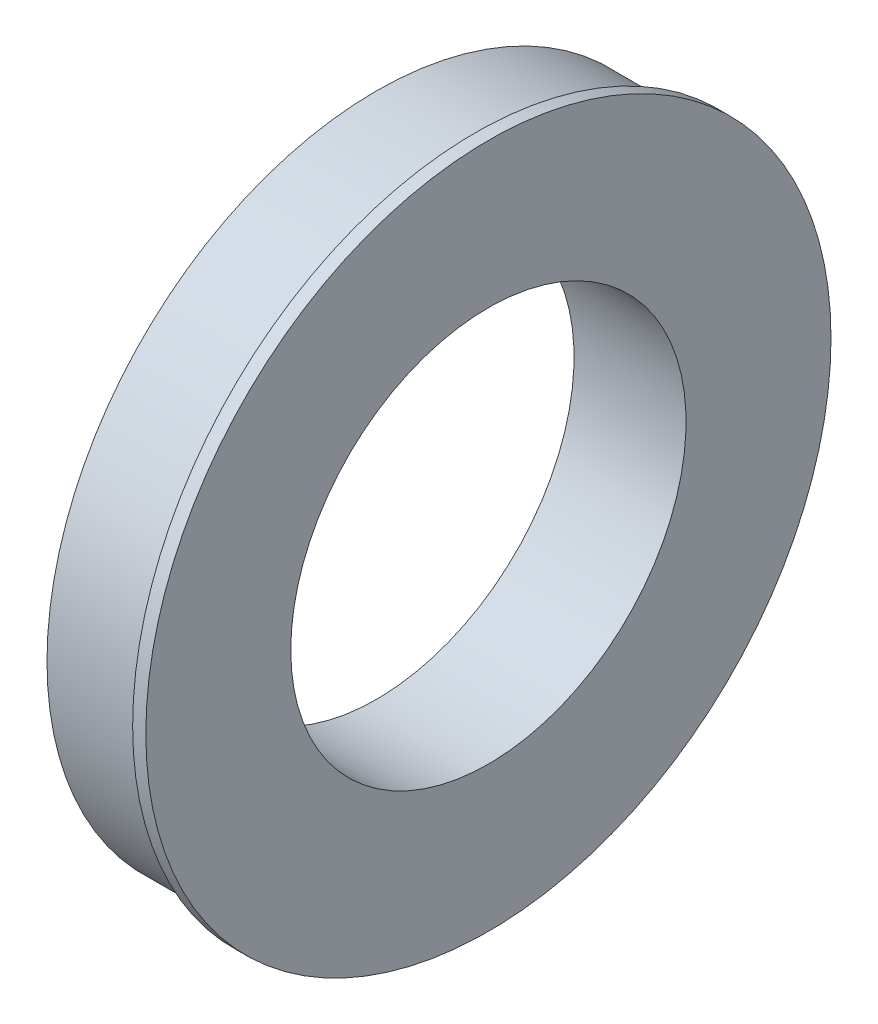
SolidWorks part; units mm, degrees
ref_plane "Front Plane" through (0, 0, 0) normal (0, 0, 1) x (1, 0, 0)
ref_plane "Top Plane" through (0, 0, 0) normal (0, 1, 0) x (1, 0, 0)
ref_plane "Right Plane" through (0, 0, 0) normal (1, 0, 0) x (0, 0, -1)
sketch "Sketch1" plane through (0, 0, 0) normal (1, 0, 0) x (0, 0, -1)
  circle A0 centre (0, 0) radius 63.5
  circle A1 centre (0, 0) radius 38.1
  dimension "D1" = 127
  dimension "D2" = 76.2
extrude "Boss-Extrude1" add sketch "Sketch1" along normal blind 19.05
sketch "Sketch2" plane through (19.05, 0, 0) normal (1, 0, 0) x (0, 0, -1)
  circle A1 centre (0, 0) radius 38.1 construction
  circle A2 centre (0, 0) radius 66.04
  circle A3 centre (0, 0) radius 66.04
  circle A4 centre (0, 0) radius 38.1
  dimension "D1" = 2.54
extrude "Boss-Extrude2" add sketch "Sketch2" along normal blind 2.54
